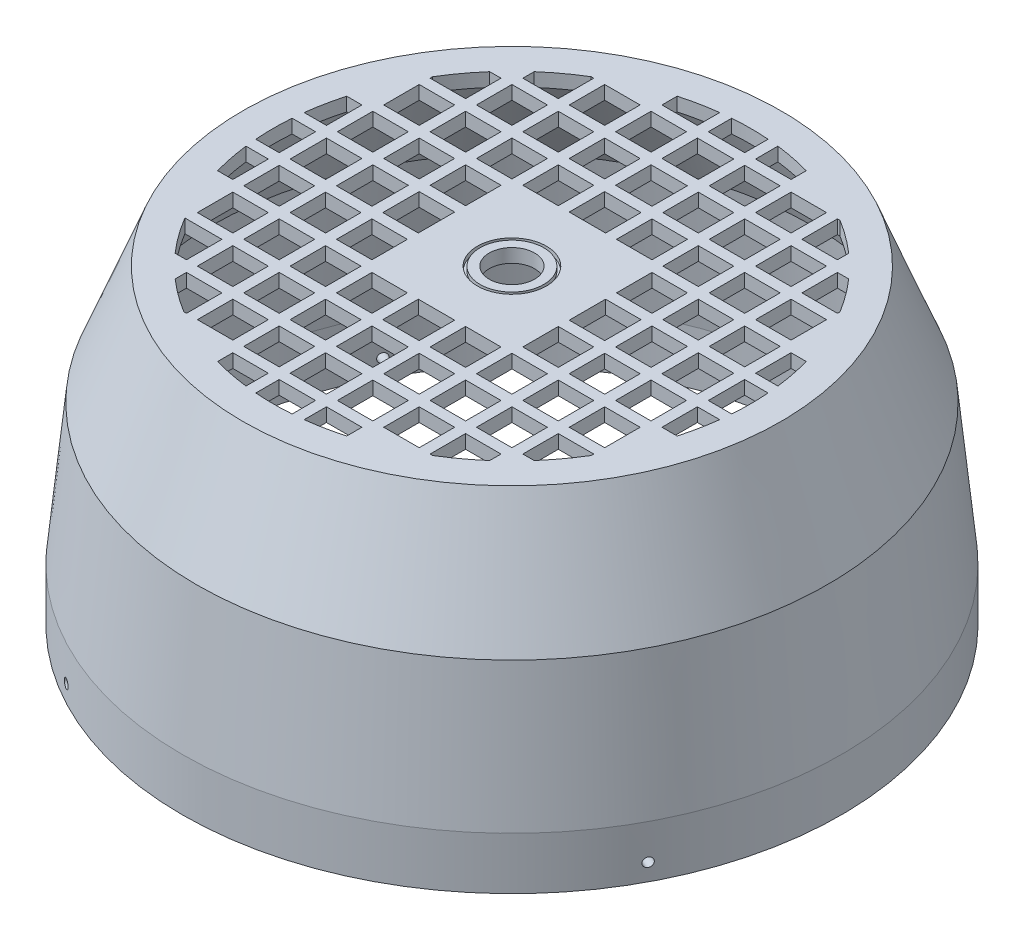
SolidWorks part; units mm, degrees
material "ABS"
ref_plane "Front Plane" through (0, 0, 0) normal (0, 0, 1) x (1, 0, 0)
ref_plane "Top Plane" through (0, 0, 0) normal (0, 1, 0) x (1, 0, 0)
ref_plane "Right Plane" through (0, 0, 0) normal (1, 0, 0) x (0, 0, -1)
sketch "Sketch1" plane through (0, 0, 0) normal (0, 0, 1) x (1, 0, 0)
  line L0 (-69.5, 0) -> (-72.5, 0)
  line L1 (-72.5, 0) -> (-72.5, 11.5)
  line L2 (-72.5, 11.5) -> (-69.4, 42.3)
  line L3 (-69.4, 42.3) -> (-59.2, 68.3)
  line L4 (-59.2, 68.3) -> (0, 68.3)
  line L5 (0, 68.3) -> (0, 65.3)
  line L6 (-69.5, 0) -> (-69.5, 11.8751)
  line L7 (-69.5, 11.8751) -> (-66.4, 42.6751)
  line L8 (-66.4, 42.6751) -> (-57.2871, 65.3)
  line L9 (-57.2871, 65.3) -> (0, 65.3)
  line L10 (0, 77.0737) -> (0, -14.0446) construction
  dimension "D2" = 11.5
  dimension "D3" = 30.8
  dimension "D4" = 26
  dimension "D5" = 59.2
  dimension "D6" = 69.4
  dimension "D7" = 3
  dimension "D9" = 3
  dimension "D10" = 3
revolve "Revolve3" add sketch "Sketch1" angle 360 about L10
sketch "Sketch2" plane through (0, 68.3, 0) normal (0, 1, 0) x (1, 0, 0)
  line L0 (4.9497, -4.9497) -> (5.374, -5.374) construction
  line L5 (-5.374, 5.374) -> (-4.9497, 4.9497) construction
  line L6 (-5.374, -5.374) -> (-4.9497, -4.9497) construction
  line L7 (4.9497, 4.9497) -> (5.374, 5.374) construction
  circle A1 centre (0, 0) radius 7.6
  circle A2 centre (0, 0) radius 7
extrude "Cut-Extrude2" cut sketch "Sketch2" against normal blind 1 contours A1 A2
sketch "Sketch4" plane through (0, 68.3, 0) normal (0, 1, 0) x (1, 0, 0)
  line L0 (-14.2, 24.4) -> (-6.4, 24.4)
  line L1 (-14.2, 16.6) -> (-6.4, 16.6)
  line L2 (-16.6, 14.2) -> (-16.6, 6.4)
  line L3 (-14.2, -16.6) -> (-6.4, -16.6)
  line L4 (16.6, 14.2) -> (16.6, 6.4)
  line L5 (26.8, -4) -> (34.6, -4)
  line L6 (14.2, -16.6) -> (14.2, -24.4)
  line L7 (-16.6, 49.8065) -> (-16.6, 47.2)
  line L8 (-14.2, 50.5431) -> (-14.2, 47.2)
  line L9 (-14.2, -16.6) -> (-14.2, -24.4)
  line L10 (14.2, 50.5431) -> (14.2, 47.2)
  line L11 (16.6, 49.8065) -> (16.6, 47.2)
  line L12 (-6.4, 52.1084) -> (-6.4, 47.2)
  line L13 (-4, -52.3474) -> (-4, -47.2)
  line L14 (4, -52.3474) -> (4, -47.2)
  line L15 (6.4, 52.1084) -> (6.4, 47.2)
  line L16 (-6.4, -16.6) -> (-6.4, -24.4)
  line L17 (-4, 16.6) -> (-4, 24.4)
  line L18 (4, 16.6) -> (4, 24.4)
  line L19 (6.4, -16.6) -> (6.4, -24.4)
  line L20 (-24.4, 44.8) -> (-24.4, 37)
  line L21 (-26.8, 45.1443) -> (-26.8, 37)
  line L22 (-34.6, 39.4853) -> (-34.6, 37)
  line L23 (-24.4, 34.6) -> (-16.6, 34.6)
  line L24 (-44.8, 27.3717) -> (-44.8, 26.8)
  line L25 (-47.2, 22.9872) -> (-47.2, 16.6)
  line L26 (24.4, 44.8) -> (24.4, 37)
  line L27 (26.8, 44.8) -> (26.8, 37)
  line L28 (34.6, 39.4853) -> (34.6, 37)
  line L29 (37, 34.6) -> (39.4853, 34.6)
  line L30 (44.8, 27.3717) -> (44.8, 26.8)
  line L31 (47.2, 22.9872) -> (47.2, 16.6)
  line L32 (-49.8065, 16.6) -> (-47.2, 16.6)
  line L33 (-50.5431, 14.2) -> (-47.2, 14.2)
  line L34 (-49.8065, -16.6) -> (-47.2, -16.6)
  line L35 (-50.5431, -14.2) -> (-47.2, -14.2)
  line L36 (-14.2, 16.6) -> (-6.4, 16.6)
  line L37 (-52.1084, 6.4) -> (-47.2, 6.4)
  line L38 (52.3474, 4) -> (47.2, 4)
  line L39 (52.3474, -4) -> (47.2, -4)
  line L40 (-52.1084, -6.4) -> (-47.2, -6.4)
  line L41 (-47.2, 4) -> (-52.3474, 4)
  line L42 (-44.8, 6.4) -> (-37, 6.4)
  line L43 (-44.8, 14.2) -> (-37, 14.2)
  line L44 (-44.8, 16.6) -> (-37, 16.6)
  line L45 (-47.2, 14.2) -> (-47.2, 6.4)
  line L46 (-44.8, 14.2) -> (-44.8, 6.4)
  line L47 (-37, 14.2) -> (-37, 6.4)
  line L48 (-34.6, 14.2) -> (-34.6, 6.4)
  line L49 (-26.8, 14.2) -> (-26.8, 6.4)
  line L50 (-24.4, 14.2) -> (-24.4, 6.4)
  line L51 (-24.4, 14.2) -> (-16.6, 14.2)
  line L52 (-24.4, 16.6) -> (-16.6, 16.6)
  line L53 (-34.6, 14.2) -> (-26.8, 14.2)
  line L54 (-34.6, 16.6) -> (-26.8, 16.6)
  line L55 (-26.8, 4) -> (-26.8, -4)
  line L56 (-24.4, 4) -> (-24.4, -4)
  line L57 (-26.8, 4) -> (-34.6, 4)
  line L58 (-24.4, 6.4) -> (-16.6, 6.4)
  line L59 (-47.2, -6.4) -> (-47.2, -14.2)
  line L60 (-44.8, -6.4) -> (-44.8, -14.2)
  line L61 (-44.8, -24.4) -> (-37, -24.4)
  line L62 (-45.1443, -26.8) -> (-37, -26.8)
  line L63 (-39.4853, -34.6) -> (-37, -34.6)
  line L64 (-34.6, -26.8) -> (-26.8, -26.8)
  line L65 (-27.3717, -44.8) -> (-26.8, -44.8)
  line L66 (-22.9872, -47.2) -> (-16.6, -47.2)
  line L67 (-44.8, 24.4) -> (-37, 24.4)
  line L68 (-44.8, 26.8) -> (-37, 26.8)
  line L69 (-39.4853, 34.6) -> (-37, 34.6)
  line L70 (-24.4, 37) -> (-16.6, 37)
  line L71 (-27.3717, 44.8) -> (-26.8, 44.8)
  line L72 (-22.9872, 47.2) -> (-16.6, 47.2)
  line L73 (-16.6, -47.2) -> (-16.6, -49.8065)
  line L74 (-14.2, -47.2) -> (-14.2, -50.5431)
  line L75 (-6.4, -47.2) -> (-6.4, -52.1084)
  line L76 (-4, -44.8) -> (-4, -37)
  line L77 (-16.6, 14.2) -> (-16.6, 6.4)
  line L78 (4, -44.8) -> (4, -37)
  line L79 (6.4, -47.2) -> (6.4, -52.1084)
  line L80 (14.2, -47.2) -> (14.2, -50.5431)
  line L81 (16.6, -47.2) -> (16.6, -49.8065)
  line L82 (-4, -47.2) -> (4, -47.2)
  line L83 (-4, -44.8) -> (4, -44.8)
  line L84 (6.4, -47.2) -> (14.2, -47.2)
  line L85 (6.4, -44.8) -> (14.2, -44.8)
  line L86 (16.6, -44.8) -> (24.4, -44.8)
  line L87 (16.6, -47.2) -> (22.9872, -47.2)
  line L88 (26.8, -44.8) -> (27.3717, -44.8)
  line L89 (-14.2, -44.8) -> (-6.4, -44.8)
  line L90 (-14.2, -47.2) -> (-6.4, -47.2)
  line L91 (-24.4, -44.8) -> (-16.6, -44.8)
  line L92 (-24.4, -37) -> (-16.6, -37)
  line L93 (-24.4, -34.6) -> (-16.6, -34.6)
  line L94 (-26.8, -37) -> (-26.8, -44.8)
  line L95 (-24.4, -37) -> (-24.4, -44.8)
  line L96 (-14.2, -37) -> (-6.4, -37)
  line L97 (-14.2, -34.6) -> (-6.4, -34.6)
  line L98 (-16.6, -37) -> (-16.6, -44.8)
  line L99 (-14.2, -37) -> (-14.2, -44.8)
  line L100 (-6.4, -37) -> (-6.4, -44.8)
  line L101 (-4, -34.6) -> (-4, -26.8)
  line L102 (-16.6, 4) -> (-16.6, -4)
  line L103 (4, -34.6) -> (4, -26.8)
  line L104 (6.4, -37) -> (6.4, -44.8)
  line L105 (-4, -34.6) -> (4, -34.6)
  line L106 (-4, -37) -> (4, -37)
  line L107 (6.4, -37) -> (14.2, -37)
  line L108 (6.4, -34.6) -> (14.2, -34.6)
  line L109 (16.6, -34.6) -> (24.4, -34.6)
  line L110 (16.6, -37) -> (24.4, -37)
  line L111 (14.2, -37) -> (14.2, -44.8)
  line L112 (16.6, -37) -> (16.6, -44.8)
  line L113 (24.4, -37) -> (24.4, -44.8)
  line L114 (26.8, -37) -> (26.8, -44.8)
  line L115 (26.8, -34.6) -> (34.6, -34.6)
  line L116 (26.8, -37) -> (34.6, -37)
  line L117 (34.6, -37) -> (34.6, -39.4853)
  line L118 (37, -37) -> (37, -37.2458)
  line L119 (37, -34.6) -> (39.4853, -34.6)
  line L120 (37, -37) -> (37.2458, -37)
  line L121 (37, -24.4) -> (44.8, -24.4)
  line L122 (37, -26.8) -> (44.8, -26.8)
  line L123 (34.6, -26.8) -> (34.6, -34.6)
  line L124 (37, -26.8) -> (37, -34.6)
  line L125 (37, -14.2) -> (44.8, -14.2)
  line L126 (37, -16.6) -> (44.8, -16.6)
  line L127 (34.6, -16.6) -> (34.6, -24.4)
  line L128 (37, -16.6) -> (37, -24.4)
  line L129 (44.8, -26.8) -> (44.8, -27.3717)
  line L130 (47.2, -16.6) -> (49.8065, -16.6)
  line L131 (47.2, -14.2) -> (50.5431, -14.2)
  line L132 (44.8, -16.6) -> (44.8, -24.4)
  line L133 (47.2, -16.6) -> (47.2, -22.9872)
  line L134 (24.4, -16.6) -> (24.4, -24.4)
  line L135 (26.8, -16.6) -> (26.8, -24.4)
  line L136 (26.8, -16.6) -> (34.6, -16.6)
  line L137 (26.8, -14.2) -> (34.6, -14.2)
  line L138 (16.6, -16.6) -> (24.4, -16.6)
  line L139 (16.6, -16.6) -> (16.6, -24.4)
  line L140 (16.6, -26.8) -> (24.4, -26.8)
  line L141 (16.6, -24.4) -> (24.4, -24.4)
  line L142 (14.2, -26.8) -> (14.2, -34.6)
  line L143 (16.6, -26.8) -> (16.6, -34.6)
  line L144 (24.4, -26.8) -> (24.4, -34.6)
  line L145 (26.8, -26.8) -> (26.8, -34.6)
  line L146 (26.8, -26.8) -> (34.6, -26.8)
  line L147 (26.8, -24.4) -> (34.6, -24.4)
  line L148 (6.4, -26.8) -> (14.2, -26.8)
  line L149 (6.4, -24.4) -> (14.2, -24.4)
  line L150 (6.4, -26.8) -> (6.4, -34.6)
  line L151 (4, -24.4) -> (4, -16.6)
  line L152 (-4, -24.4) -> (-4, -16.6)
  line L153 (-6.4, -26.8) -> (-6.4, -34.6)
  line L154 (-4, -26.8) -> (4, -26.8)
  line L155 (-4, -24.4) -> (4, -24.4)
  line L156 (-16.6, -26.8) -> (-16.6, -34.6)
  line L157 (-14.2, -26.8) -> (-14.2, -34.6)
  line L158 (-14.2, -26.8) -> (-6.4, -26.8)
  line L159 (-14.2, -24.4) -> (-6.4, -24.4)
  line L160 (-24.4, -26.8) -> (-16.6, -26.8)
  line L161 (-24.4, -24.4) -> (-16.6, -24.4)
  line L162 (-26.8, -26.8) -> (-26.8, -34.6)
  line L163 (-24.4, -26.8) -> (-24.4, -34.6)
  line L164 (-34.6, -37) -> (-26.8, -37)
  line L165 (-34.6, -34.6) -> (-26.8, -34.6)
  line L166 (-34.6, -24.4) -> (-26.8, -24.4)
  line L167 (-34.6, -37) -> (-34.6, -39.4853)
  line L168 (-37, -26.8) -> (-37, -34.6)
  line L169 (-34.6, -26.8) -> (-34.6, -34.6)
  line L170 (-34.6, -16.6) -> (-26.8, -16.6)
  line L171 (-34.6, -14.2) -> (-26.8, -14.2)
  line L172 (-37, -16.6) -> (-37, -24.4)
  line L173 (-34.6, -16.6) -> (-34.6, -24.4)
  line L174 (-26.8, -16.6) -> (-26.8, -24.4)
  line L175 (-24.4, -16.6) -> (-24.4, -24.4)
  line L176 (-16.6, -16.6) -> (-16.6, -24.4)
  line L177 (-14.2, -16.6) -> (-6.4, -16.6)
  line L178 (16.6, -6.4) -> (24.4, -6.4)
  line L179 (-16.6, -4) -> (-24.4, -4)
  line L180 (-16.6, 4) -> (-16.6, -4)
  line L181 (-16.6, 4) -> (-24.4, 4)
  line L182 (16.6, 6.4) -> (24.4, 6.4)
  line L183 (-16.6, -6.4) -> (-16.6, -14.2)
  line L184 (-16.6, -6.4) -> (-16.6, -14.2)
  line L185 (16.6, -14.2) -> (24.4, -14.2)
  line L186 (6.4, -16.6) -> (14.2, -16.6)
  line L187 (6.4, -16.6) -> (14.2, -16.6)
  line L188 (-4, -16.6) -> (4, -16.6)
  line L189 (-4, -16.6) -> (4, -16.6)
  line L190 (-4, -24.4) -> (14.2, -24.4)
  line L191 (16.6, -24.4) -> (24.4, -24.4)
  line L192 (47.2, -6.4) -> (52.1084, -6.4)
  line L193 (44.8, -4) -> (37, -4)
  line L194 (37, -6.4) -> (44.8, -6.4)
  line L196 (24.4, -4) -> (16.6, -4)
  line L197 (26.8, -6.4) -> (34.6, -6.4)
  line L198 (16.6, -6.4) -> (16.6, -14.2)
  line L199 (16.6, -6.4) -> (16.6, -14.2)
  line L200 (24.4, -6.4) -> (24.4, -14.2)
  line L201 (26.8, -6.4) -> (26.8, -14.2)
  line L202 (34.6, -6.4) -> (34.6, -14.2)
  line L203 (37, -6.4) -> (37, -14.2)
  line L204 (44.8, -6.4) -> (44.8, -14.2)
  line L205 (47.2, -6.4) -> (47.2, -14.2)
  line L206 (24.4, 4) -> (24.4, -4)
  line L207 (26.8, 4) -> (26.8, -4)
  line L208 (34.6, 4) -> (34.6, -4)
  line L209 (37, 4) -> (37, -4)
  line L210 (44.8, 4) -> (44.8, -4)
  line L211 (47.2, 4) -> (47.2, -4)
  line L212 (16.6, 4) -> (16.6, -4)
  line L213 (16.6, 4) -> (16.6, -4)
  line L214 (26.8, 6.4) -> (34.6, 6.4)
  line L215 (24.4, 4) -> (16.6, 4)
  line L216 (37, 6.4) -> (44.8, 6.4)
  line L217 (34.6, 4) -> (26.8, 4)
  line L218 (44.8, 4) -> (37, 4)
  line L219 (47.2, 6.4) -> (52.1084, 6.4)
  line L220 (16.6, 14.2) -> (16.6, 6.4)
  line L221 (24.4, 14.2) -> (24.4, 6.4)
  line L222 (26.8, 14.2) -> (26.8, 6.4)
  line L223 (34.6, 14.2) -> (34.6, 6.4)
  line L224 (37, 14.2) -> (37, 6.4)
  line L225 (44.8, 14.2) -> (44.8, 6.4)
  line L226 (47.2, 14.2) -> (47.2, 6.4)
  line L227 (16.6, 14.2) -> (24.4, 14.2)
  line L228 (26.8, 16.6) -> (34.6, 16.6)
  line L229 (26.8, 14.2) -> (34.6, 14.2)
  line L230 (37, 16.6) -> (44.8, 16.6)
  line L231 (37, 14.2) -> (44.8, 14.2)
  line L232 (47.2, 16.6) -> (49.8065, 16.6)
  line L233 (47.2, 14.2) -> (50.5431, 14.2)
  line L234 (26.8, 24.4) -> (34.6, 24.4)
  line L235 (26.8, 26.8) -> (34.6, 26.8)
  line L236 (37, 24.4) -> (44.8, 24.4)
  line L237 (37, 26.8) -> (44.8, 26.8)
  line L238 (44.8, 24.4) -> (44.8, 16.6)
  line L239 (34.6, 24.4) -> (34.6, 16.6)
  line L240 (37, 24.4) -> (37, 16.6)
  line L241 (24.4, 24.4) -> (24.4, 16.6)
  line L242 (26.8, 24.4) -> (26.8, 16.6)
  line L243 (14.2, 24.4) -> (14.2, 16.6)
  line L244 (16.6, 24.4) -> (16.6, 16.6)
  line L245 (16.6, 26.8) -> (24.4, 26.8)
  line L246 (16.6, 24.4) -> (24.4, 24.4)
  line L247 (16.6, 16.6) -> (24.4, 16.6)
  line L248 (6.4, 16.6) -> (14.2, 16.6)
  line L249 (6.4, 16.6) -> (14.2, 16.6)
  line L250 (6.4, 24.4) -> (14.2, 24.4)
  line L251 (6.4, 26.8) -> (14.2, 26.8)
  line L252 (4, 26.8) -> (4, 34.6)
  line L253 (6.4, 24.4) -> (6.4, 16.6)
  line L254 (-4, 16.6) -> (4, 16.6)
  line L255 (-4, 16.6) -> (4, 16.6)
  line L256 (-4, 24.4) -> (4, 24.4)
  line L257 (-4, 26.8) -> (4, 26.8)
  line L258 (-6.4, 24.4) -> (-6.4, 16.6)
  line L259 (-4, 26.8) -> (-4, 34.6)
  line L260 (-24.4, -14.2) -> (-16.6, -14.2)
  line L261 (-24.4, -6.4) -> (-16.6, -6.4)
  line L262 (-26.8, -4) -> (-34.6, -4)
  line L263 (-26.8, -6.4) -> (-26.8, -14.2)
  line L264 (-24.4, -6.4) -> (-24.4, -14.2)
  line L265 (-37, -4) -> (-44.8, -4)
  line L266 (-34.6, -6.4) -> (-26.8, -6.4)
  line L267 (-37, -6.4) -> (-37, -14.2)
  line L268 (-34.6, -6.4) -> (-34.6, -14.2)
  line L269 (-44.8, -6.4) -> (-37, -6.4)
  line L270 (-47.2, -4) -> (-52.3474, -4)
  line L271 (-37, 4) -> (-44.8, 4)
  line L272 (-34.6, 6.4) -> (-26.8, 6.4)
  line L273 (-37, 4) -> (-37, -4)
  line L274 (-34.6, 4) -> (-34.6, -4)
  line L275 (-44.8, 4) -> (-44.8, -4)
  line L276 (-47.2, 4) -> (-47.2, -4)
  line L277 (-24.4, 24.4) -> (-16.6, 24.4)
  line L278 (-24.4, -16.6) -> (-16.6, -16.6)
  line L279 (-34.6, 24.4) -> (-26.8, 24.4)
  line L280 (-34.6, 26.8) -> (-26.8, 26.8)
  line L281 (-44.8, 24.4) -> (-44.8, 16.6)
  line L282 (-26.8, 24.4) -> (-26.8, 16.6)
  line L283 (-24.4, 24.4) -> (-24.4, 16.6)
  line L284 (-37, 24.4) -> (-37, 16.6)
  line L285 (-34.6, 24.4) -> (-34.6, 16.6)
  line L286 (-16.6, 24.4) -> (-16.6, 16.6)
  line L287 (-14.2, 24.4) -> (-14.2, 16.6)
  line L288 (-37, 34.6) -> (-37, 26.8)
  line L289 (-34.6, 34.6) -> (-34.6, 26.8)
  line L290 (-34.6, 34.6) -> (-26.8, 34.6)
  line L291 (-34.6, 37) -> (-26.8, 37)
  line L292 (-26.8, 34.6) -> (-26.8, 26.8)
  line L293 (-24.4, 34.6) -> (-24.4, 26.8)
  line L294 (-16.6, 34.6) -> (-16.6, 26.8)
  line L295 (-14.2, 34.6) -> (-14.2, 26.8)
  line L296 (-14.2, 37) -> (-6.4, 37)
  line L297 (-14.2, 34.6) -> (-6.4, 34.6)
  line L298 (-4, 37) -> (4, 37)
  line L299 (-4, 34.6) -> (4, 34.6)
  line L300 (-6.4, 34.6) -> (-6.4, 26.8)
  line L301 (-4, 37) -> (-4, 44.8)
  line L302 (-34.6, -24.4) -> (-26.8, -24.4)
  line L303 (4, 37) -> (4, 44.8)
  line L304 (6.4, 34.6) -> (6.4, 26.8)
  line L305 (6.4, 34.6) -> (14.2, 34.6)
  line L306 (6.4, 37) -> (14.2, 37)
  line L307 (16.6, 37) -> (24.4, 37)
  line L308 (16.6, 34.6) -> (24.4, 34.6)
  line L309 (14.2, 34.6) -> (14.2, 26.8)
  line L310 (16.6, 34.6) -> (16.6, 26.8)
  line L311 (24.4, 34.6) -> (24.4, 26.8)
  line L312 (26.8, 34.6) -> (26.8, 26.8)
  line L313 (26.8, 37) -> (34.6, 37)
  line L314 (26.8, 34.6) -> (34.6, 34.6)
  line L315 (34.6, 34.6) -> (34.6, 26.8)
  line L316 (37, 34.6) -> (37, 26.8)
  line L317 (26.8, 44.8) -> (27.3717, 44.8)
  line L318 (16.6, 44.8) -> (16.6, 37)
  line L319 (14.2, 44.8) -> (14.2, 37)
  line L320 (16.6, 47.2) -> (22.9872, 47.2)
  line L321 (16.6, 44.8) -> (24.4, 44.8)
  line L322 (4, 47.2) -> (4, 52.3474)
  line L323 (6.4, 44.8) -> (6.4, 37)
  line L324 (6.4, 47.2) -> (14.2, 47.2)
  line L325 (6.4, 44.8) -> (14.2, 44.8)
  line L326 (-6.4, 44.8) -> (-6.4, 37)
  line L327 (-4, 47.2) -> (-4, 52.3474)
  line L328 (-4, 47.2) -> (4, 47.2)
  line L329 (-4, 44.8) -> (4, 44.8)
  line L330 (-16.6, 44.8) -> (-16.6, 37)
  line L331 (-14.2, 44.8) -> (-14.2, 37)
  line L332 (-14.2, 47.2) -> (-6.4, 47.2)
  line L333 (-14.2, 44.8) -> (-6.4, 44.8)
  line L334 (-24.4, 44.8) -> (-16.6, 44.8)
  line L335 (-44.8, -14.2) -> (-37, -14.2)
  line L336 (-44.8, -16.6) -> (-37, -16.6)
  line L337 (-47.2, -16.6) -> (-47.2, -22.9872)
  line L338 (-44.8, -16.6) -> (-44.8, -24.4)
  line L339 (37, -24.4) -> (44.8, -24.4)
  line L340 (26.8, -24.4) -> (34.6, -24.4)
  line L341 (-24.4, -24.4) -> (-16.6, -24.4)
  line L342 (-14.2, -24.4) -> (-6.4, -24.4)
  line L343 (-24.4, 26.8) -> (-16.6, 26.8)
  line L344 (-14.2, 26.8) -> (-6.4, 26.8)
  circle A0 centre (0, 0) radius 52.5
extrude "Cut-Extrude6" cut sketch "Sketch4" against normal through all contours L71 A0 L22 L291 L21 | L334 L20 L70 L330 | L333 L331 L296 L326 | L329 L301 L298 L303 | L325 L323 L306 L319 | L321 L318 L307 L26 | L28 A0 L317 L27 L313 | L10 A0 L15 L324 | L322 A0 L327 L328 | L12 A0 L8 L332 | L69 A0 L24 L68 L288 | L292 L290 L289 L280 | L293 L343 L294 L23 | L295 L344 L300 L297 | L299 L259 L257 L252 | L309 L305 L304 L251 | L311 L308 L310 L245 | L315 L314 L312 L235 | L30 A0 L29 L316 L237 | L236 L240 L230 L238 | L234 L242 L228 L239 | L244 L247 L241 L246 | L250 L253 L248 L243 | L256 L17 L254 L18 | L0 L287 L1 L258 | L286 L277 L283 L52 | L279 L285 L54 L282 | L284 L67 L281 L44 | L33 A0 L37 L45 | L47 L43 L46 L42 | L48 L272 L49 L53 | L50 L58 L2 L51 | L227 L4 L182 L221 | L229 L222 L214 L223 | L231 L224 L216 L225 | L219 A0 L233 L226 | L336 L338 L61 L172 | L271 L275 L265 L273 | L57 L274 L262 L55 | L102 L181 L56 L179 | L41 A0 L270 L276 | L40 A0 L35 L59 | L60 L335 L267 L269 | L266 L268 L171 L263 | L261 L264 L260 L183 | L174 L170 L173 L166 | L278 L175 L161 L176 | L188 L152 L155 L151 | L9 L159 L16 L3 | L200 L178 L198 L185 | L206 L215 L212 L196 | L208 L217 L207 L5 | L202 L197 L201 L137 | L210 L218 L209 L193 | L204 L194 L203 L125 | L39 A0 L38 L211 | L131 A0 L192 L205 | L186 L19 L149 L6 | L139 L141 L134 L138 | L135 L147 L127 L136 | L146 L145 L115 L123 | L144 L140 L143 L109 | L148 L150 L108 L142 | L154 L101 L105 L103 | L62 A0 L63 L168 | L98 L92 L95 L91 | L100 L96 L99 L89 | L111 L107 L104 L85 | L113 L110 L112 L86 | L88 A0 L117 L116 L114 | L158 L157 L97 L153 | L160 L163 L93 L156 | L74 A0 L75 L90 | L13 A0 L14 L82 | L79 A0 L80 L84 | L119 A0 L129 L122 L124 | L132 L126 L128 L121 | L167 A0 L65 L94 L164 | L64 L169 L165 L162 | L106 L76 L83 L78
sketch "Sketch5" plane through (0, 68.3, 0) normal (0, 1, 0) x (1, 0, 0)
  circle A0 centre (0, 0) radius 5
extrude "Cut-Extrude7" cut sketch "Sketch5" against normal through all
ref_plane "Plane1" through (27.6844, 0, -63.2027) normal (-0.4012, 0, 0.916) x (-0.916, 0, -0.4012)
ref_plane "Plane3" through (-63.2027, 0, -27.6844) normal (0.916, 0, 0.4012) x (-0.4012, 0, 0.916)
ref_plane "Plane4" through (27.6844, 0, -63.2027) normal (-0.4012, 0, 0.916) x (-0.916, 0, -0.4012)
sketch "Sketch10" plane through (27.6844, 0, -63.2027) normal (-0.4012, 0, 0.916) x (-0.916, 0, -0.4012)
  circle A0 centre (-5.5, -3.7581) radius 1
ref_plane "Plane5" through (-63.2027, 0, -27.6844) normal (0.916, 0, 0.4012) x (-0.4012, 0, 0.916)
extrude "Cut-Extrude14" cut sketch "Sketch10" against normal blind 10
pattern_circular "CirPattern2" count 4 over 360 about axis through (0, 0, 0) along (0, 1, 0) of "Cut-Extrude14"
